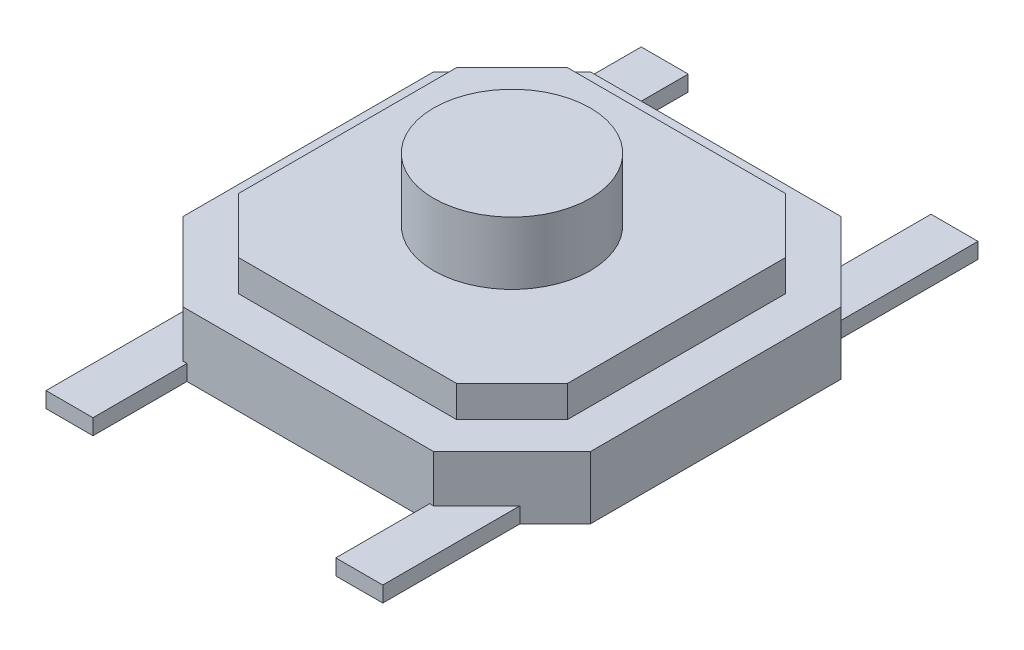
SolidWorks part; units mm, degrees
ref_plane "前视" through (0, 0, 0) normal (0, 0, 1) x (1, 0, 0)
ref_plane "上视" through (0, 0, 0) normal (0, 1, 0) x (1, 0, 0)
ref_plane "右视" through (0, 0, 0) normal (1, 0, 0) x (0, 0, -1)
sketch "草图1" plane through (0, 0, 0) normal (0, 1, 0) x (1, 0, 0)
  line L0 (0, 96.9306) -> (0, -101.3275) construction
  line L1 (-119.7143, 0) -> (134.9034, 0) construction
  line L3 (-2.6, 2.6) -> (2.6, 2.6)
  line L4 (-2.6, 2.6) -> (-2.6, -2.6)
  line L5 (-2.6, -2.6) -> (2.6, -2.6)
  line L6 (2.6, 2.6) -> (2.6, -2.6)
  dimension "D1" = 5.2
  dimension "D2" = 5.2
extrude "拉伸1" add sketch "草图1" along normal blind 0.8
chamfer "倒角1" distance 1 angle 45 4 edges at (2.6, 0.4, -2.6) (2.6, 0.4, 2.6) (-2.6, 0.4, 2.6) (-2.6, 0.4, -2.6)
sketch "草图3" plane through (0, 0.8, 0) normal (0, 1, 0) x (1, 0, 0)
  line L16 (-2.1, 1.3929) -> (-2.1, -1.3929)
  line L17 (-2.1, -1.3929) -> (-1.3929, -2.1)
  line L18 (-1.3929, -2.1) -> (1.3929, -2.1)
  line L19 (1.3929, -2.1) -> (2.1, -1.3929)
  line L20 (2.1, -1.3929) -> (2.1, 1.3929)
  line L21 (2.1, 1.3929) -> (1.3929, 2.1)
  line L22 (1.3929, 2.1) -> (-1.3929, 2.1)
  line L23 (-1.3929, 2.1) -> (-2.1, 1.3929)
  line L24 (-2.1, 1.3929) -> (-2.1, -1.3929)
  line L25 (-2.1, -1.3929) -> (-1.3929, -2.1)
  line L26 (-1.3929, -2.1) -> (1.3929, -2.1)
  line L27 (1.3929, -2.1) -> (2.1, -1.3929)
  line L28 (2.1, -1.3929) -> (2.1, 1.3929)
  line L29 (2.1, 1.3929) -> (1.3929, 2.1)
  line L30 (1.3929, 2.1) -> (-1.3929, 2.1)
  line L31 (-1.3929, 2.1) -> (-2.1, 1.3929)
  dimension "D1" = 0.5
extrude "凸台-拉伸1" add sketch "草图3" along normal offset from surface (0.4 mm away) 1.2 up to face at (0, 0, 0)
sketch "草图2" plane through (0, 1.2, 0) normal (0, 1, 0) x (-1, 0, 0)
  line L0 (-2.6, 0) -> (8.7109, 0) construction
  line L1 (-2.6, 1.6) -> (-2.6, -1.6) construction
  line L2 (0, -7.8518) -> (0, 10.0992) construction
  circle A0 centre (0, 0) radius 1
  dimension "D1" = 2
extrude "高度" add sketch "草图2" along normal offset from surface (0.8 mm away) 2 up to face at (0, 0, 0)
sketch "草图4" plane through (0, 0, 0) normal (0, -1, 0) x (1, 0, 0)
  line L0 (0, 5.6043) -> (0, -6.529) construction
  line L1 (-7.8223, 0) -> (5.922, 0) construction
  line L3 (-1.55, 1.1317) -> (-2.15, 1.1317)
  line L4 (-1.55, 1.1317) -> (-1.55, 3.8)
  line L5 (-1.55, 3.8) -> (-2.15, 3.8)
  line L6 (-2.15, 1.1317) -> (-2.15, 3.8)
  line L7 (-1.85, 4.1914) -> (-1.85, 0.5446) construction
  line L8 (1.85, 4.1914) -> (1.85, 0.5446) construction
  line L9 (2.15, 1.1317) -> (2.15, 3.8)
  line L10 (1.55, 3.8) -> (2.15, 3.8)
  line L11 (1.55, 1.1317) -> (1.55, 3.8)
  line L12 (1.55, 1.1317) -> (2.15, 1.1317)
  line L13 (1.85, -4.1914) -> (1.85, -0.5446) construction
  line L14 (-1.85, -4.1914) -> (-1.85, -0.5446) construction
  line L15 (1.55, -1.1317) -> (2.15, -1.1317)
  line L16 (1.55, -1.1317) -> (1.55, -3.8)
  line L17 (1.55, -3.8) -> (2.15, -3.8)
  line L18 (2.15, -1.1317) -> (2.15, -3.8)
  line L19 (-2.15, -1.1317) -> (-2.15, -3.8)
  line L20 (-1.55, -3.8) -> (-2.15, -3.8)
  line L21 (-1.55, -1.1317) -> (-1.55, -3.8)
  line L22 (-1.55, -1.1317) -> (-2.15, -1.1317)
  dimension "D1" = 0.6
  dimension "D2" = 7.6
  dimension "D3" = 3.7
extrude "凸台-拉伸2" add sketch "草图4" against normal blind 0.2
